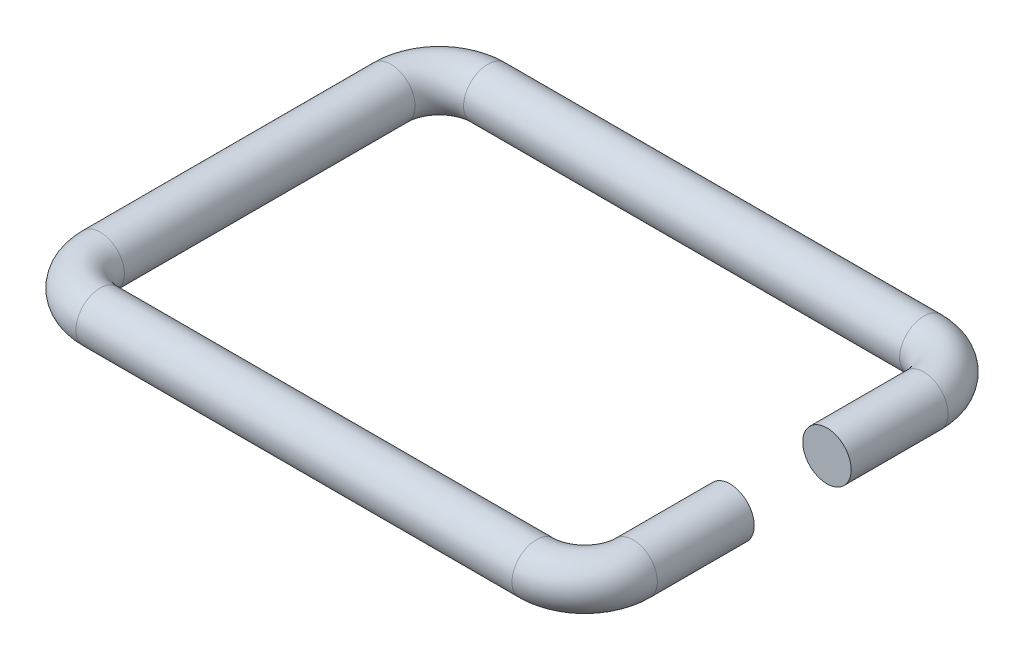
SolidWorks part; units mm, degrees
ref_plane "Plan de face" through (0, 0, 0) normal (0, 0, 1) x (1, 0, 0)
ref_plane "Plan de dessus" through (0, 0, 0) normal (0, 1, 0) x (1, 0, 0)
ref_plane "Plan de droite" through (0, 0, 0) normal (1, 0, 0) x (0, 0, -1)
sketch "Esquisse1" plane through (0, 0, 0) normal (0, 0, 1) x (1, 0, 0)
  circle A0 centre (0, 0) radius 1.25
  dimension "D1" = 2.5
sketch "Esquisse2" plane through (0, 0, 0) normal (0, 1, 0) x (1, 0, 0)
  line L0 (0, 0) -> (0, 5)
  line L1 (-2.5, 7.5) -> (-25, 7.5)
  line L2 (-27.5, 5) -> (-27.5, -10)
  line L3 (-25, -12.5) -> (-2.5, -12.5)
  line L4 (0, -10) -> (0, -5)
  line L5 (0, 0) -> (0, -5) construction
  arc A0 (-27.5, -10) -> (-25, -12.5) centre (-25, -10) ccw
  arc A1 (-2.5, -12.5) -> (0, -10) centre (-2.5, -10) ccw
  arc A2 (0, 5) -> (-2.5, 7.5) centre (-2.5, 5) ccw
  arc A3 (-25, 7.5) -> (-27.5, 5) centre (-25, 5) ccw
  point P9 (-27.5, -12.5)
  point P12 (0, -12.5)
  dimension "D4" = 2.5
  dimension "D1" = 20
  dimension "D2" = 27.5
  dimension "D3" = 5
sweep "Balayage1" add profiles "Esquisse1" path "Esquisse2"
